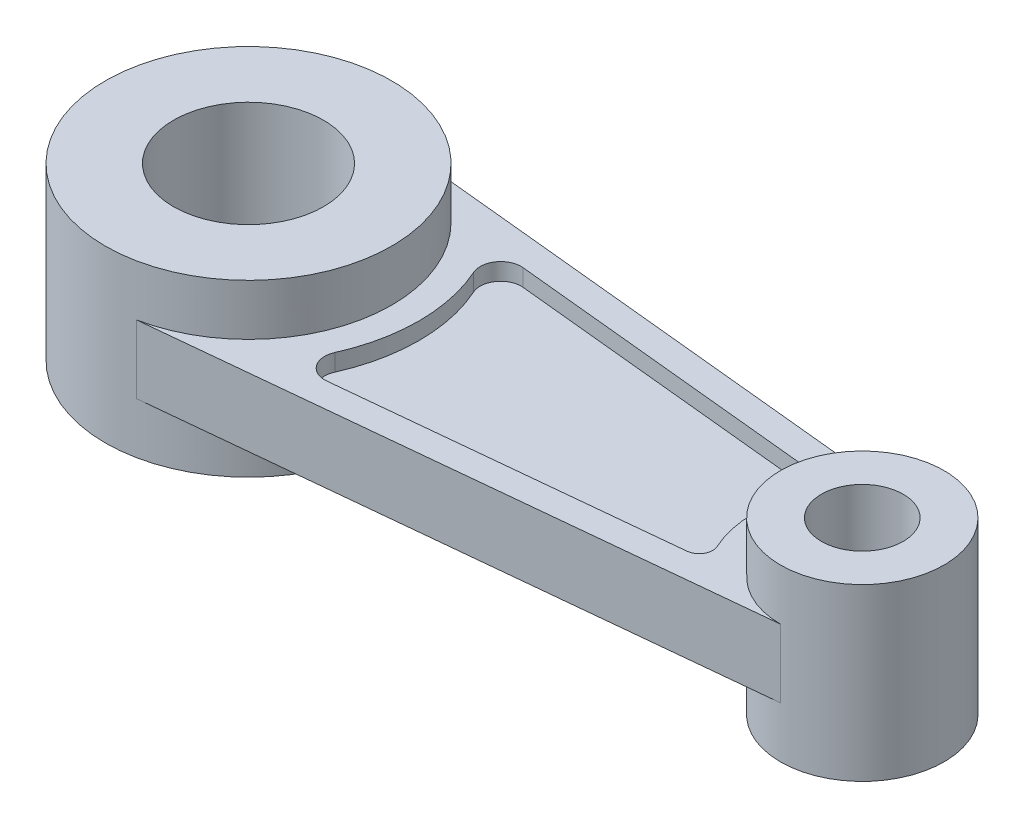
SolidWorks part; units mm, degrees
ref_plane "Front Plane" through (0, 0, 0) normal (0, 0, 1) x (1, 0, 0)
ref_plane "Top Plane" through (0, 0, 0) normal (0, 1, 0) x (1, 0, 0)
ref_plane "Right Plane" through (0, 0, 0) normal (1, 0, 0) x (0, 0, -1)
sketch "Sketch1" plane through (0, 0, 0) normal (0, 1, 0) x (1, 0, 0)
  line L0 (0, 21) -> (90, 12)
  line L1 (0, -21) -> (90, -12)
  arc A0 (0, 21) -> (0, -21) centre (0, 0) ccw
  arc A1 (90, -12) -> (90, 12) centre (90, 0) ccw
  dimension "D1" = 42
  dimension "D2" = 24
  dimension "D3" = 90
extrude "Boss-Extrude1" add sketch "Sketch1" against normal blind 10 contours L1 A1 L0 A0
sketch "Sketch2" plane through (0, 0, 0) normal (0, 1, 0) x (1, 0, 0)
  circle A0 centre (0, 0) radius 21
  circle A2 centre (90, 0) radius 12
  dimension "D1" = 24
  dimension "D2" = 42
extrude "Boss-Extrude2" add sketch "Sketch2" against normal blind 17.5
sketch "Sketch3" plane through (0, 0, 0) normal (0, 1, 0) x (1, 0, 0)
  circle A0 centre (0, 0) radius 21
  circle A1 centre (90, 0) radius 12
  dimension "D1" = 42
  dimension "D2" = 24
extrude "Boss-Extrude3" add sketch "Sketch3" along normal blind 7.5
sketch "Sketch4" plane through (0, 7.5, 0) normal (0, 1, 0) x (1, 0, 0)
  circle A0 centre (0, 0) radius 11
  circle A1 centre (90, 0) radius 6
  dimension "D1" = 22
  dimension "D2" = 12
extrude "Cut-Extrude1" cut sketch "Sketch4" against normal blind 38.5
sketch "Sketch5" plane through (0, 0, 0) normal (0, 1, 0) x (1, 0, 0)
  line L0 (4.1584, 20.5842) -> (90, 12) construction
  line L2 (4.1584, -20.5842) -> (90, -12) construction
  line L4 (25.8691, 14.3931) -> (73.8829, 9.5918)
  line L5 (25.8691, -14.3931) -> (73.8829, -9.5918)
  arc A1 (75.4968, 6.7571) -> (75.4968, -6.7571) centre (90, 0) ccw
  arc A2 (22.8309, -10.1857) -> (22.8309, 10.1857) centre (0, 0) ccw
  arc A3 (25.8691, 14.3931) -> (22.8309, 10.1857) centre (25.5706, 11.408) ccw
  arc A4 (25.8691, -14.3931) -> (22.8309, -10.1857) centre (25.5706, -11.408) cw
  arc A5 (75.4968, 6.7571) -> (73.8829, 9.5918) centre (73.6839, 7.6017) ccw
  arc A6 (75.4968, -6.7571) -> (73.8829, -9.5918) centre (73.6839, -7.6017) cw
  dimension "D1" = 25
  dimension "D2" = 32
  dimension "D5" = 3
  dimension "D6" = 3
  dimension "D7" = 2
  dimension "D8" = 2
  dimension "D3" = 4
  dimension "D4" = 4
extrude "Cut-Extrude2" cut sketch "Sketch5" against normal blind 2.5
sketch "Sketch7" plane through (0, -10, 0) normal (0, -1, 0) x (1, 0, 0)
  line L0 (4.1584, 20.5842) -> (90, 12) construction
  line L2 (4.1584, -20.5842) -> (90, -12) construction
  line L3 (25.8691, 14.3931) -> (73.8829, 9.5918)
  line L4 (25.8691, -14.3931) -> (73.8829, -9.5918)
  arc A1 (75.4968, 6.7571) -> (75.4968, -6.7571) centre (90, 0) ccw
  arc A2 (22.8309, -10.1857) -> (22.8309, 10.1857) centre (0, 0) ccw
  arc A3 (75.4968, 6.7571) -> (73.8829, 9.5918) centre (73.6839, 7.6017) ccw
  arc A4 (75.4968, -6.7571) -> (73.8829, -9.5918) centre (73.6839, -7.6017) cw
  arc A5 (25.8691, 14.3931) -> (22.8309, 10.1857) centre (25.5706, 11.408) ccw
  arc A6 (25.8691, -14.3931) -> (22.8309, -10.1857) centre (25.5706, -11.408) cw
  dimension "D1" = 25
  dimension "D2" = 32
  dimension "D5" = 2
  dimension "D6" = 2
  dimension "D7" = 3
  dimension "D8" = 3
  dimension "D3" = 4
  dimension "D4" = 4
extrude "Cut-Extrude3" cut sketch "Sketch7" against normal blind 2.5
